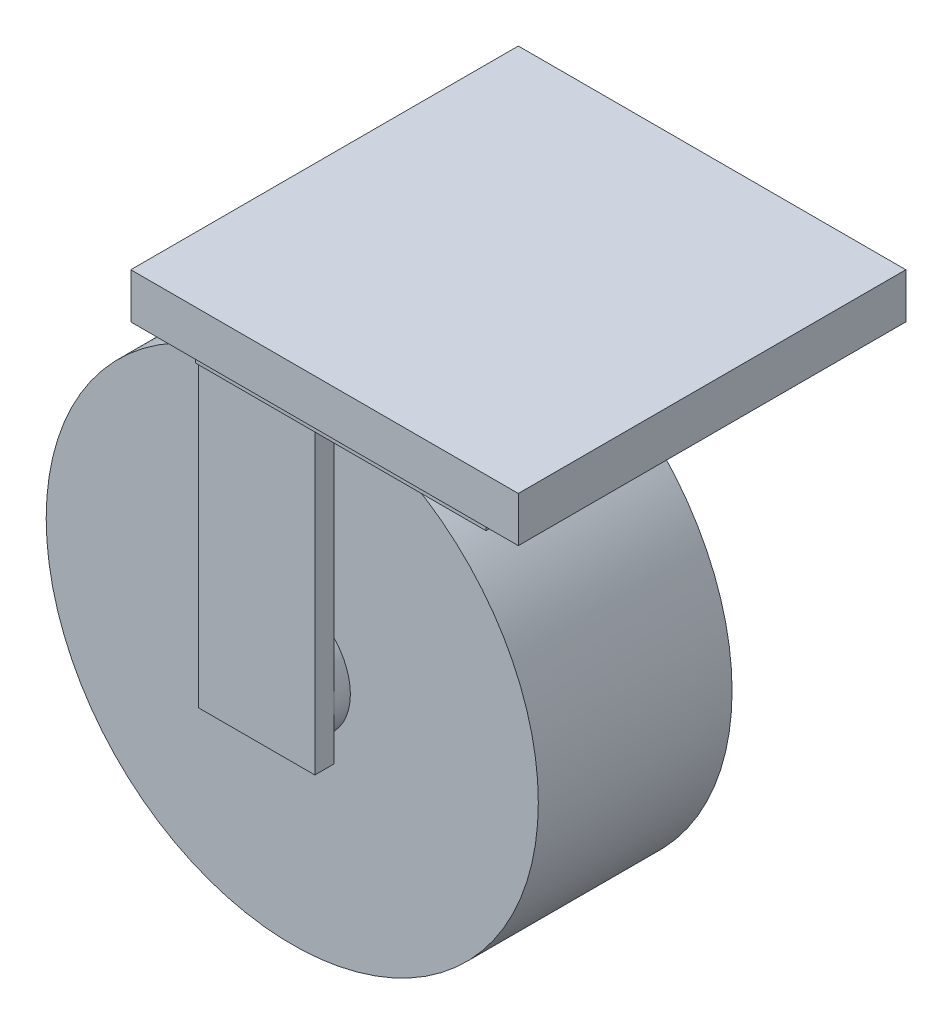
SolidWorks part; units mm, degrees
ref_plane "Front Plane" through (0, 0, 0) normal (0, 0, 1) x (1, 0, 0)
ref_plane "Top Plane" through (0, 0, 0) normal (0, 1, 0) x (1, 0, 0)
ref_plane "Right Plane" through (0, 0, 0) normal (1, 0, 0) x (0, 0, -1)
sketch "SK_P01_Spacer4mm" plane through (0, 0, 0) normal (0, 1, 0) x (1, 0, 0)
  line L0 (-15.95, -30) -> (44.05, -30)
  line L1 (44.05, -30) -> (44.05, 30)
  line L2 (44.05, 30) -> (-15.95, 30)
  line L3 (-15.95, 30) -> (-15.95, -30)
extrude "P01_Spacer4mm" add sketch "SK_P01_Spacer4mm" along normal blind 4 from offset 89
sketch "SK_P02_Topplate" plane through (0, 0, 0) normal (0, 1, 0) x (1, 0, 0)
  line L0 (-15.95, -30) -> (44.05, -30)
  line L1 (44.05, -30) -> (44.05, 30)
  line L2 (44.05, 30) -> (-15.95, 30)
  line L3 (-15.95, 30) -> (-15.95, -30)
extrude "P02_Topplate" add sketch "SK_P02_Topplate" along normal blind 3 from offset 86
sketch "SK_P03_Swivelrace" plane through (0, 0, 0) normal (0, 1, 0) x (1, 0, 0)
  circle A0 centre (14.05, 0) radius 22
extrude "P03_Swivelrace" add sketch "SK_P03_Swivelrace" along normal blind 6 from offset 80
sketch "SK_P04_Forkyoke" plane through (0, 0, 0) normal (0, 1, 0) x (1, 0, 0)
  line L0 (-14.95, -21) -> (30.05, -21)
  line L1 (30.05, -21) -> (30.05, 21)
  line L2 (30.05, 21) -> (-14.95, 21)
  line L3 (-14.95, 21) -> (-14.95, -21)
extrude "P04_Forkyoke" add sketch "SK_P04_Forkyoke" along normal blind 3.5 from offset 76.5
sketch "SK_P05_Forkleg" plane through (0, 0, 0) normal (0, 1, 0) x (1, 0, 0)
  line L0 (-14.95, 17.5) -> (3.05, 17.5)
  line L1 (3.05, 17.5) -> (3.05, 20.5)
  line L2 (3.05, 20.5) -> (-14.95, 20.5)
  line L3 (-14.95, 20.5) -> (-14.95, 17.5)
extrude "P05_Forkleg" add sketch "SK_P05_Forkleg" along normal blind 48 from offset 30
sketch "SK_P06_Forkleg" plane through (0, 0, 0) normal (0, 1, 0) x (1, 0, 0)
  line L0 (-14.95, -20.5) -> (3.05, -20.5)
  line L1 (3.05, -20.5) -> (3.05, -17.5)
  line L2 (3.05, -17.5) -> (-14.95, -17.5)
  line L3 (-14.95, -17.5) -> (-14.95, -20.5)
extrude "P06_Forkleg" add sketch "SK_P06_Forkleg" along normal blind 48 from offset 30
sketch "SK_P07_Wheel3in" plane through (0, 0, 0) normal (0, 0, 1) x (1, 0, 0)
  circle A0 centre (-5.95, 38.1) radius 38.1
extrude "P07_Wheel3in" add sketch "SK_P07_Wheel3in" along normal blind 30 from offset 15
sketch "SK_P08_Axle" plane through (0, 0, 0) normal (0, 0, 1) x (1, 0, 0)
  circle A0 centre (-5.95, 38.1) radius 9
extrude "P08_Axle" add sketch "SK_P08_Axle" along normal blind 35 from offset 17.5
